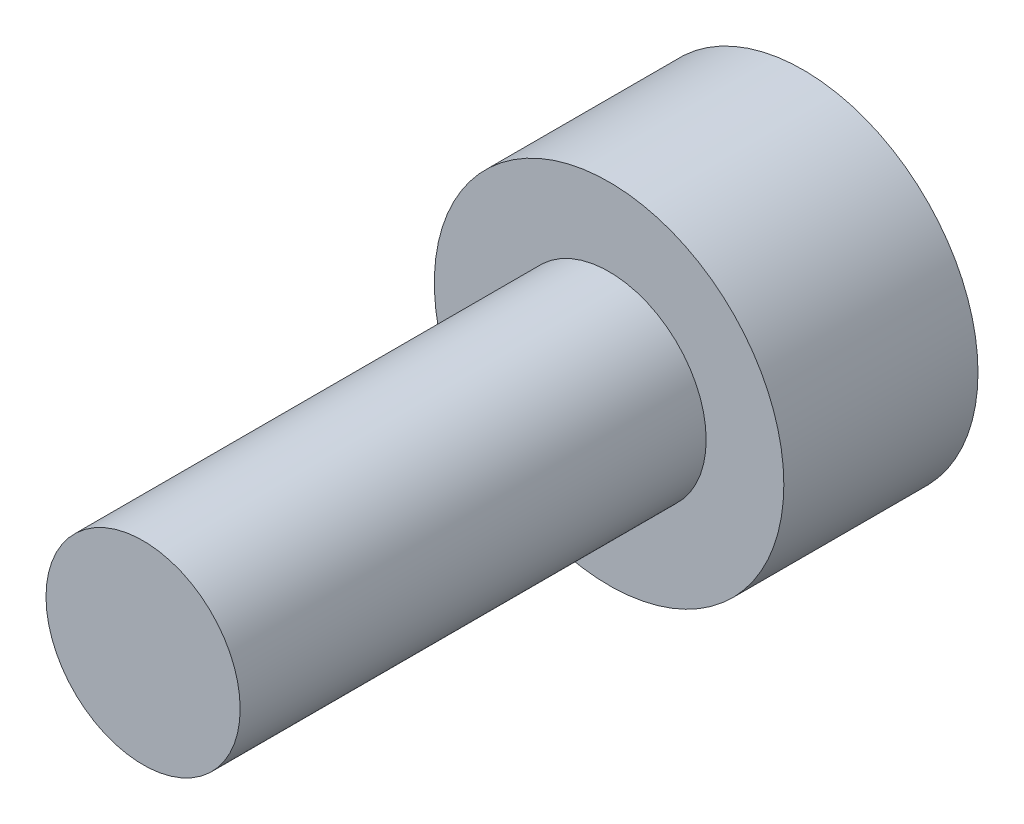
SolidWorks part; units mm, degrees
material "AISI 304"
ref_plane "Alzado" through (0, 0, 0) normal (0, 0, 1) x (1, 0, 0)
ref_plane "Planta" through (0, 0, 0) normal (0, 1, 0) x (1, 0, 0)
ref_plane "Vista lateral" through (0, 0, 0) normal (1, 0, 0) x (0, 0, -1)
sketch "Sk_Cabeza" plane through (0, 0, 0) normal (0, 0, 1) x (1, 0, 0)
  circle A0 centre (0, 0) radius 2.25
  dimension "D1" = 4.5
extrude "Cabeza" add sketch "Sk_Cabeza" along normal blind 2.5 from offset 2.5
sketch "Sk_Cuerpo" plane through (0, 0, 0) normal (0, 0, 1) x (1, 0, 0)
  circle A0 centre (0, 0) radius 1.25
  dimension "D1" = 2.5
extrude "Cuerpo" add sketch "Sk_Cuerpo" along normal blind 6
sketch "Sk_Hexagono_interior" plane through (0, 0, 0) normal (0, 0, 1) x (1, 0, 0)
  line L1 (0, -1.1547) -> (1, -0.5774)
  line L2 (1, -0.5774) -> (1, 0.5774)
  line L3 (1, 0.5774) -> (0, 1.1547)
  line L4 (0, 1.1547) -> (-1, 0.5774)
  line L5 (-1, 0.5774) -> (-1, -0.5774)
  line L6 (-1, -0.5774) -> (0, -1.1547)
  circle A0 centre (0, 0) radius 1 construction
  dimension "D1" = 2
extrude "Hexagono_interior" cut sketch "Sk_Hexagono_interior" along normal blind 1.25 from offset 2.5
